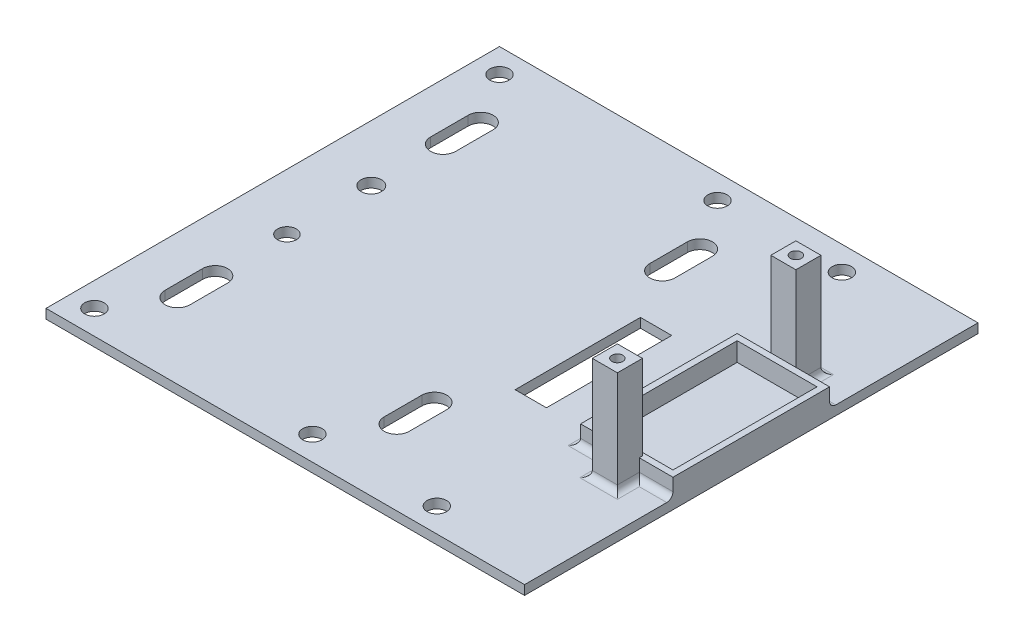
SolidWorks part; units mm, degrees
ref_plane "Přední rovina" through (0, 0, 0) normal (0, 0, 1) x (1, 0, 0)
ref_plane "Horní rovina" through (0, 0, 0) normal (0, 1, 0) x (1, 0, 0)
ref_plane "Pravá rovina" through (0, 0, 0) normal (1, 0, 0) x (0, 0, -1)
sketch "Sketch1" plane through (0, 0, 0) normal (0, 1, 0) x (1, 0, 0)
  line L0 (0, 0) -> (0, 36.2) construction
  line L1 (-31.2, 36.2) -> (31.2, 36.2)
  line L2 (-31.2, 36.2) -> (-31.2, -36.2)
  line L3 (-31.2, -36.2) -> (31.2, -36.2)
  line L4 (31.2, 36.2) -> (31.2, -36.2)
  line L5 (-31.2, 36.2) -> (31.2, -36.2) construction
  line L6 (-31.2, -36.2) -> (31.2, 36.2) construction
  line L7 (31.2, 36.2) -> (45.2, 36.2)
  line L8 (31.2, 36.2) -> (31.2, -36.2)
  line L9 (31.2, -36.2) -> (45.2, -36.2)
  line L10 (45.2, 36.2) -> (45.2, -36.2)
  line L11 (0, 0) -> (-31.2, 0) construction
  circle A0 centre (-27.333, 32.333) radius 1.55
  circle A1 centre (27.333, 32.333) radius 1.55
  circle A2 centre (27.333, -32.333) radius 1.55
  circle A3 centre (-27.333, -32.333) radius 1.55
  point P0 (0, 0)
  dimension "D4" = 3.1
  dimension "D1" = 72.4
  dimension "D2" = 62.4
  dimension "D3" = 14
  dimension "D5" = 3.867
  dimension "D6" = 3.867
extrude "Boss-Extrude1" add sketch "Sketch1" along normal blind 1.5 contours L4 L1 L2 L3 | L10 L7 L4 L9
sketch "Sketch3" plane through (0, 1.5, 0) normal (0, 1, 0) x (1, 0, 0)
  line L0 (45.2, 36.2) -> (45.2, -36.2) construction
  line L1 (45.2, 12.5) -> (30.45, 12.5)
  line L2 (45.2, 12.5) -> (45.2, -12.5)
  line L3 (45.2, -12.5) -> (30.45, -12.5)
  line L4 (30.45, 12.5) -> (30.45, -12.5)
  line L5 (31.45, 11.5) -> (31.45, -11.5)
  line L6 (44.2, -11.5) -> (31.45, -11.5)
  line L7 (44.2, 11.5) -> (44.2, -11.5)
  line L8 (44.2, 11.5) -> (31.45, 11.5)
  point P6 (30.45, 0)
  dimension "D1" = 25
  dimension "D2" = 14.75
  dimension "D4" = 23
  dimension "D5" = 12.75
  dimension "D3" = 1
extrude "Boss-Extrude2" add sketch "Sketch3" along normal blind 3
sketch "Sketch4" plane through (0, 1.5, 0) normal (0, 1, 0) x (1, 0, 0)
  line L0 (30.45, -12.5) -> (45.2, -12.5) construction
  line L1 (35.825, -12) -> (39.825, -12)
  line L2 (35.825, -12) -> (35.825, -16)
  line L3 (35.825, -16) -> (39.825, -16)
  line L4 (39.825, -12) -> (39.825, -16)
  line L6 (31.45, -11.5) -> (44.2, -11.5) construction
  line L8 (35.825, 16.5) -> (39.825, 16.5)
  line L9 (35.825, 16.5) -> (35.825, 12.5)
  line L10 (35.825, 12.5) -> (39.825, 12.5)
  line L11 (39.825, 16.5) -> (39.825, 12.5)
  line L12 (45.2, 12.5) -> (30.45, 12.5) construction
  line L13 (44.2, 11.5) -> (31.45, 11.5) construction
  point P6 (37.825, -12)
  point P7 (37.825, -12.5)
  point P8 (39.825, -14)
  point P15 (37.825, 12.5)
  point P18 (37.825, 12.5)
  point P19 (39.825, 14.5)
  dimension "D1" = 4
  dimension "D2" = 4
  dimension "D3" = 2.5
  dimension "D4" = 4
  dimension "D5" = 4
  dimension "D6" = 3
extrude "Boss-Extrude3" add sketch "Sketch4" along normal blind 16.5
sketch "Sketch5" plane through (0, 18, 0) normal (0, 1, 0) x (1, 0, 0)
  line L0 (35.825, -12) -> (39.825, -16) construction
  line L1 (35.825, -16) -> (39.825, -16) construction
  line L2 (39.825, 12.5) -> (35.825, 16.5) construction
  circle A0 centre (37.825, -14) radius 0.875
  circle A1 centre (37.825, 14.5) radius 0.875
  dimension "D1" = 1.75
  dimension "D2" = 1.75
extrude "Cut-Extrude1" cut sketch "Sketch5" against normal blind 4
fillet "Fillet1" radius 1 11 edges at (42.5125, 1.5, 12.5) (33.1375, 1.5, 12.5) (42.5125, 1.5, -12.5) (33.1375, 1.5, -12.5) (35.825, 1.5, -14.5) (39.825, 1.5, -14.5) (37.825, 1.5, -16.5) (30.45, 1.5, 0) (35.825, 1.5, 14.25) (39.825, 1.5, 14.25) (37.825, 1.5, 16)
sketch "Sketch6" plane through (0, 1.5, 0) normal (0, 1, 0) x (1, 0, 0)
  line L0 (7.473, -32.333) -> (27.333, -32.333) construction
  line L4 (7.473, 32.333) -> (27.333, 32.333) construction
  circle A4 centre (7.473, -32.333) radius 1.55
  circle A5 centre (27.333, -32.333) radius 1.55 construction
  circle A6 centre (7.473, 32.333) radius 1.55
  dimension "D2" = 19.86
  dimension "D4" = 19.86
  dimension "D1" = 3.1
  dimension "D3" = 3.1
extrude "Cut-Extrude5" cut sketch "Sketch6" against normal through all contours A4 | A6
sketch "Sketch7" plane through (0, 1.5, 0) normal (0, 1, 0) x (1, 0, 0)
  line L1 (17.5, 10) -> (22.5, 10)
  line L2 (17.5, 10) -> (17.5, -10)
  line L3 (17.5, -10) -> (22.5, -10)
  line L4 (22.5, 10) -> (22.5, -10)
  line L5 (17.5, 10) -> (22.5, -10) construction
  line L6 (17.5, -10) -> (22.5, 10) construction
  point P0 (20, 0)
  dimension "D1" = 20
  dimension "D2" = 5
  dimension "D3" = 20
extrude "Cut-Extrude3" cut sketch "Sketch7" against normal through all
sketch "Sketch8" plane through (0, 0, 0) normal (0, -1, 0) x (1, 0, 0)
  line L0 (-22.2, -6.73) -> (-22.2, 6.73) construction
  line L1 (-31.2, -36.2) -> (-31.2, 36.2) construction
  circle A0 centre (-22.2, -6.73) radius 1.5
  circle A1 centre (-22.2, 6.73) radius 1.5
  point P4 (-22.2, 0)
  dimension "D1" = 3
  dimension "D2" = 3
  dimension "D3" = 13.46
  dimension "D4" = 9
extrude "Cut-Extrude4" cut sketch "Sketch8" against normal through all
sketch "Sketch9" plane through (0, 1.5, 0) normal (0, 1, 0) x (1, 0, 0)
  line L0 (-22.2, 24.2) -> (-22.2, 18.2) construction
  line L1 (-20.2, 24.2) -> (-20.2, 18.2)
  line L2 (-24.2, 24.2) -> (-24.2, 18.2)
  line L3 (-22.2, -18.2) -> (-22.2, -24.2) construction
  line L4 (-20.2, -18.2) -> (-20.2, -24.2)
  line L5 (-24.2, -18.2) -> (-24.2, -24.2)
  line L6 (-22.2, 2.3889) -> (-22.2, -13.5415) construction
  line L7 (-31.2, 36.2) -> (45.2, 36.2) construction
  line L8 (-31.2, -36.2) -> (45.2, -36.2) construction
  line L9 (-4.7, 36.2) -> (-4.7, -36.2) construction
  line L10 (12.8, 24.2) -> (12.8, 18.2) construction
  line L11 (10.8, 24.2) -> (10.8, 18.2)
  line L12 (14.8, 24.2) -> (14.8, 18.2)
  line L13 (12.8, -18.2) -> (12.8, -24.2) construction
  line L14 (10.8, -18.2) -> (10.8, -24.2)
  line L15 (14.8, -18.2) -> (14.8, -24.2)
  arc A0 (-20.2, 24.2) -> (-24.2, 24.2) centre (-22.2, 24.2) ccw
  arc A1 (-24.2, 18.2) -> (-20.2, 18.2) centre (-22.2, 18.2) ccw
  arc A2 (-20.2, -18.2) -> (-24.2, -18.2) centre (-22.2, -18.2) ccw
  arc A3 (-24.2, -24.2) -> (-20.2, -24.2) centre (-22.2, -24.2) ccw
  circle A6 centre (-22.2, 6.73) radius 1.6367
  arc A7 (10.8, 24.2) -> (14.8, 24.2) centre (12.8, 24.2) cw
  arc A8 (14.8, 18.2) -> (10.8, 18.2) centre (12.8, 18.2) cw
  arc A9 (10.8, -18.2) -> (14.8, -18.2) centre (12.8, -18.2) cw
  arc A10 (14.8, -24.2) -> (10.8, -24.2) centre (12.8, -24.2) cw
  point P2 (-22.2, 21.2)
  point P7 (-22.2, -21.2)
  point P27 (12.8, 21.2)
  point P34 (12.8, -21.2)
  dimension "D1" = 2
  dimension "D2" = 2
  dimension "D3" = 6
  dimension "D4" = 6
  dimension "D5" = 15
  dimension "D6" = 15
  dimension "D7" = 17.5
extrude "Cut-Extrude6" cut sketch "Sketch9" against normal through all
